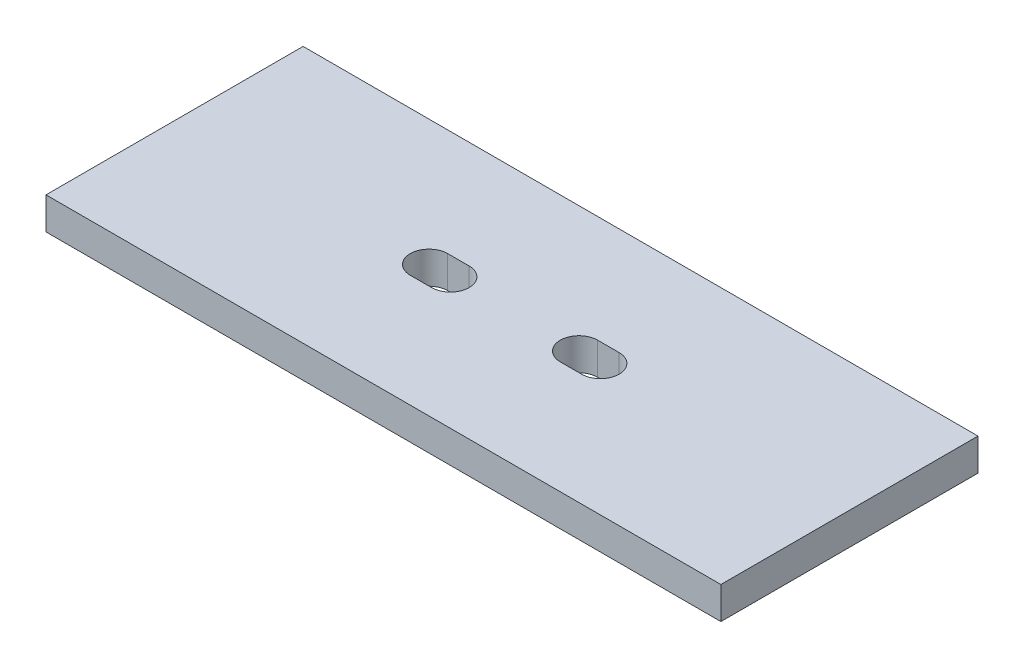
SolidWorks part; units mm, degrees
ref_plane "前视基准面" through (0, 0, 0) normal (0, 0, 1) x (1, 0, 0)
ref_plane "上视基准面" through (0, 0, 0) normal (0, 1, 0) x (1, 0, 0)
ref_plane "右视基准面" through (0, 0, 0) normal (1, 0, 0) x (0, 0, -1)
sketch "草图1" plane through (0, 0, 0) normal (0, 1, 0) x (1, 0, 0)
  line L1 (-31.5, 12) -> (31.5, 12)
  line L2 (-31.5, 12) -> (-31.5, -12)
  line L3 (-31.5, -12) -> (31.5, -12)
  line L4 (31.5, 12) -> (31.5, -12)
  line L5 (-31.5, 12) -> (31.5, -12) construction
  line L6 (-31.5, -12) -> (31.5, 12) construction
  point P0 (0, 0)
  dimension "D1" = 24
  dimension "D2" = 63
extrude "凸台-拉伸1" add sketch "草图1" along normal blind 3
sketch "草图2" plane through (0, 3, 0) normal (0, 1, 0) x (1, 0, 0)
  line L0 (-31.5, -12) -> (31.5, -12) construction
  line L1 (-6, 0.25) -> (-8, 0.25) construction
  line L2 (-6, -1.5) -> (-8, -1.5)
  line L3 (-6, 2) -> (-8, 2)
  line L4 (6, 0.25) -> (8, 0.25) construction
  line L5 (6, 2) -> (8, 2)
  line L6 (6, -1.5) -> (8, -1.5)
  arc A0 (-6, -1.5) -> (-6, 2) centre (-6, 0.25) ccw
  arc A1 (-8, 2) -> (-8, -1.5) centre (-8, 0.25) ccw
  arc A2 (6, 2) -> (6, -1.5) centre (6, 0.25) ccw
  arc A3 (8, -1.5) -> (8, 2) centre (8, 0.25) ccw
  point P0 (0, -12)
  point P5 (-7, 0.25)
  point P10 (7, 0.25)
  point P19 (0.7395, 0.25)
  dimension "D2" = 1.75
  dimension "D1" = 10.5
  dimension "D3" = 2
  dimension "D4" = 14
  dimension "D5" = 7
extrude "切除-拉伸1" cut sketch "草图2" against normal blind 3
